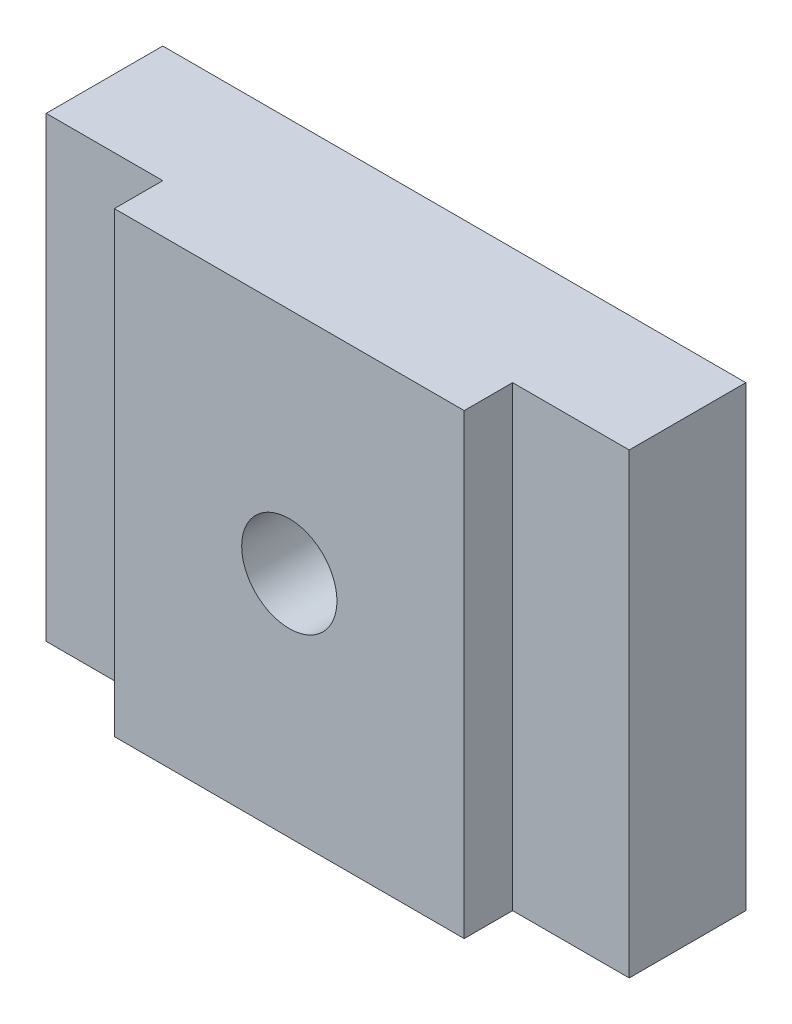
SolidWorks part; units mm, degrees
ref_plane "Front Plane" through (0, 0, 0) normal (0, 0, 1) x (1, 0, 0)
ref_plane "Top Plane" through (0, 0, 0) normal (0, 1, 0) x (1, 0, 0)
ref_plane "Right Plane" through (0, 0, 0) normal (1, 0, 0) x (0, 0, -1)
sketch "Sketch1" plane through (0, 0, 0) normal (0, 1, 0) x (1, 0, 0)
  line L0 (0, 0) -> (0, 238960.5535) construction
  line L1 (7.65, 0) -> (-7.65, 0)
  line L2 (-7.65, 0) -> (-7.65, 2.1167)
  line L3 (-7.65, 2.1167) -> (-12.75, 2.1167)
  line L4 (-12.75, 2.1167) -> (-12.75, 7.2167)
  line L5 (-12.75, 7.2167) -> (12.75, 7.2167)
  line L6 (12.75, 2.1167) -> (12.75, 7.2167)
  line L7 (7.65, 2.1167) -> (12.75, 2.1167)
  line L8 (7.65, 0) -> (7.65, 2.1167)
  point P11 (0, 7.2167)
  point P13 (0, 0)
  dimension "D1" = 15.3
  dimension "D2" = 25.5
  dimension "D3" = 2.1167
  dimension "D4" = 5.1
extrude "Boss-Extrude1" add sketch "Sketch1" along normal blind 20
sketch "Sketch2" plane through (0, 0, -7.2167) normal (0, 0, -1) x (-1, 0, 0)
  line L0 (0, 20) -> (0, -49980) construction
  line L1 (-12.75, 20) -> (12.75, 20) construction
  line L2 (-12.75, 10) -> (-50012.75, 10) construction
  line L3 (-12.75, 20) -> (-12.75, 0) construction
  circle A0 centre (0, 10) radius 2.0828
  point P4 (0, 20)
  point P9 (-12.75, 10)
  dimension "D1" = 4.1656
extrude "Cut-Extrude1" cut sketch "Sketch2" against normal through all
